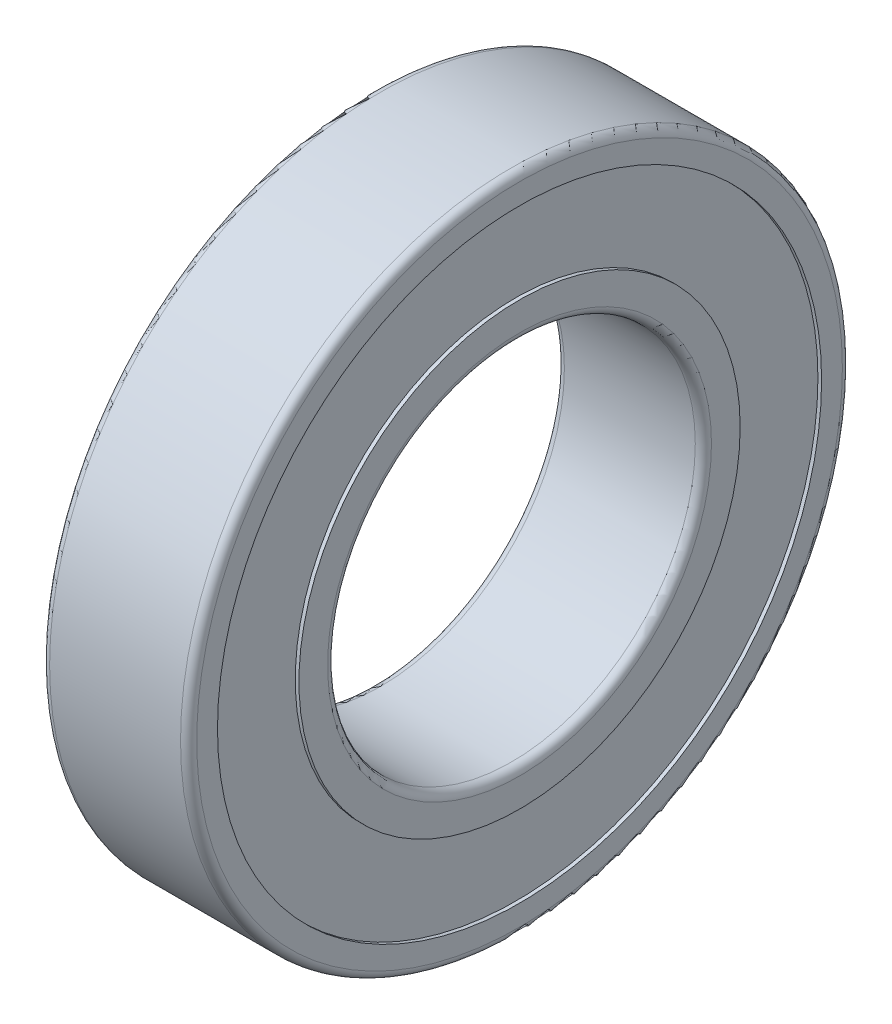
SolidWorks part; units mm, degrees
material "Plain Carbon Steel"
ref_plane "Front Plane" through (0, 0, 0) normal (0, 0, 1) x (1, 0, 0)
ref_plane "Top Plane" through (0, 0, 0) normal (0, 1, 0) x (1, 0, 0)
ref_plane "Right Plane" through (0, 0, 0) normal (1, 0, 0) x (0, 0, -1)
sketch "Sketch1" plane through (0, 0, 0) normal (0, 0, 1) x (1, 0, 0)
  line L0 (0, 0) -> (13.7268, 0) construction
  line L1 (0, 25) -> (0, 30)
  line L2 (0, 30) -> (0.5, 30)
  line L3 (0.5, 30) -> (0.5, 41.075)
  line L4 (0.5, 41.075) -> (0, 41.075)
  line L5 (0, 41.075) -> (0, 45)
  line L6 (0, 45) -> (20, 45)
  line L7 (20, 45) -> (20, 41.075)
  line L8 (20, 41.075) -> (19.5, 41.075)
  line L9 (19.5, 41.075) -> (19.5, 30)
  line L10 (19.5, 30) -> (20, 30)
  line L11 (20, 30) -> (20, 25)
  line L12 (20, 25) -> (0, 25)
  dimension "D1" = 50
  dimension "D2" = 90
  dimension "D3" = 82.15
  dimension "D4" = 60
  dimension "D5" = 0.5
  dimension "D6" = 0.5
  dimension "D7" = 20
revolve "Revolve1" add sketch "Sketch1" angle 360 about L0
fillet "Fillet1" radius 1.1 4 edges at (0, 0, 25) (20, 0, 25) (20, 0, 45) (0, 0, 45)
move or copy body "Body-Move/Copy1" bodies to move or copy 101
